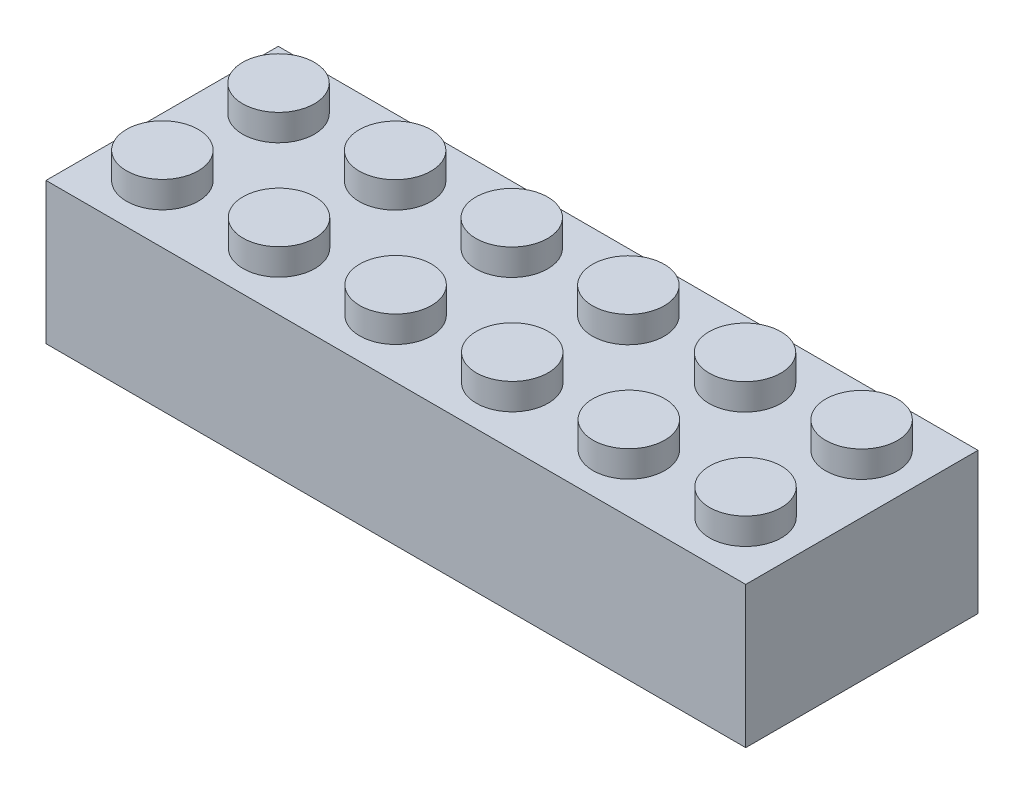
SolidWorks part; units mm, degrees
ref_plane "Front Plane" through (0, 0, 0) normal (0, 0, 1) x (1, 0, 0)
ref_plane "Top Plane" through (0, 0, 0) normal (0, 1, 0) x (1, 0, 0)
ref_plane "Right Plane" through (0, 0, 0) normal (1, 0, 0) x (0, 0, -1)
sketch "Sketch1" plane through (0, 0, 0) normal (0, 1, 0) x (1, 0, 0)
  line L1 (-23.875, 7.925) -> (23.875, 7.925)
  line L2 (-23.875, 7.925) -> (-23.875, -7.925)
  line L3 (-23.875, -7.925) -> (23.875, -7.925)
  line L4 (23.875, 7.925) -> (23.875, -7.925)
  line L5 (-23.875, 7.925) -> (23.875, -7.925) construction
  line L6 (-23.875, -7.925) -> (23.875, 7.925) construction
  point P0 (0, 0)
  dimension "D1" = 15.85
  dimension "D2" = 47.75
extrude "Boss-Extrude1" add sketch "Sketch1" against normal blind 9.65
sketch "Sketch2" plane through (0, 0, 0) normal (0, 1, 0) x (1, 0, 0)
  line L1 (-23.875, 7.925) -> (-23.875, -7.925) construction
  line L2 (23.875, 7.925) -> (-23.875, 7.925) construction
  line L3 (23.875, -7.925) -> (23.875, 7.925) construction
  circle A0 centre (-19.8958, 3.9625) radius 2.45
  circle A1 centre (-11.9375, 3.9625) radius 2.45
  circle A2 centre (-3.9792, 3.9625) radius 2.45
  circle A3 centre (3.9792, 3.9625) radius 2.45
  circle A4 centre (11.9375, 3.9625) radius 2.45
  circle A5 centre (19.8958, 3.9625) radius 2.45
  circle A6 centre (-11.9375, -3.9625) radius 2.45
  circle A7 centre (-3.9792, -3.9625) radius 2.45
  circle A8 centre (3.9792, -3.9625) radius 2.45
  circle A9 centre (11.9375, -3.9625) radius 2.45
  circle A10 centre (19.8958, -3.9625) radius 2.45
  circle A11 centre (-19.8958, -3.9625) radius 2.45
  dimension "D1" = 4.9
  dimension "D6" = 7.9583
  dimension "D7" = 7.925
  dimension "D8" = 3.9792
  dimension "D2" = 3.9792
  dimension "D3" = 3.9625
  dimension "D4" = 6
  dimension "D5" = 2
extrude "Boss-Extrude2" add sketch "Sketch2" along normal blind 1.8
shell "Shell1" thickness 1.2
sketch "Sketch3" plane through (0, -1.2, 0) normal (0, -1, 0) x (1, 0, 0)
  line L0 (23.875, -7.925) -> (-23.875, -7.925) construction
  line L2 (-23.875, -7.925) -> (-23.875, 7.925) construction
  circle A0 centre (-15.9167, 0) radius 3.25
  circle A1 centre (-15.9167, 0) radius 2.33
  circle A2 centre (-7.9583, 0) radius 2.33
  circle A3 centre (-7.9583, 0) radius 3.25
  circle A4 centre (0, 0) radius 2.33
  circle A5 centre (0, 0) radius 3.25
  circle A6 centre (7.9583, 0) radius 2.33
  circle A7 centre (7.9583, 0) radius 3.25
  circle A8 centre (15.9167, 0) radius 2.33
  circle A9 centre (15.9167, 0) radius 3.25
  dimension "D1" = 6.5
  dimension "D2" = 4.66
  dimension "D4" = 7.9583
  dimension "D6" = 7.9583
  dimension "D3" = 7.925
  dimension "D5" = 5
extrude "Boss-Extrude3" add sketch "Sketch3" along normal offset from surface (8.25 mm away) 0.2 up to face at (0, -9.65, 0)
